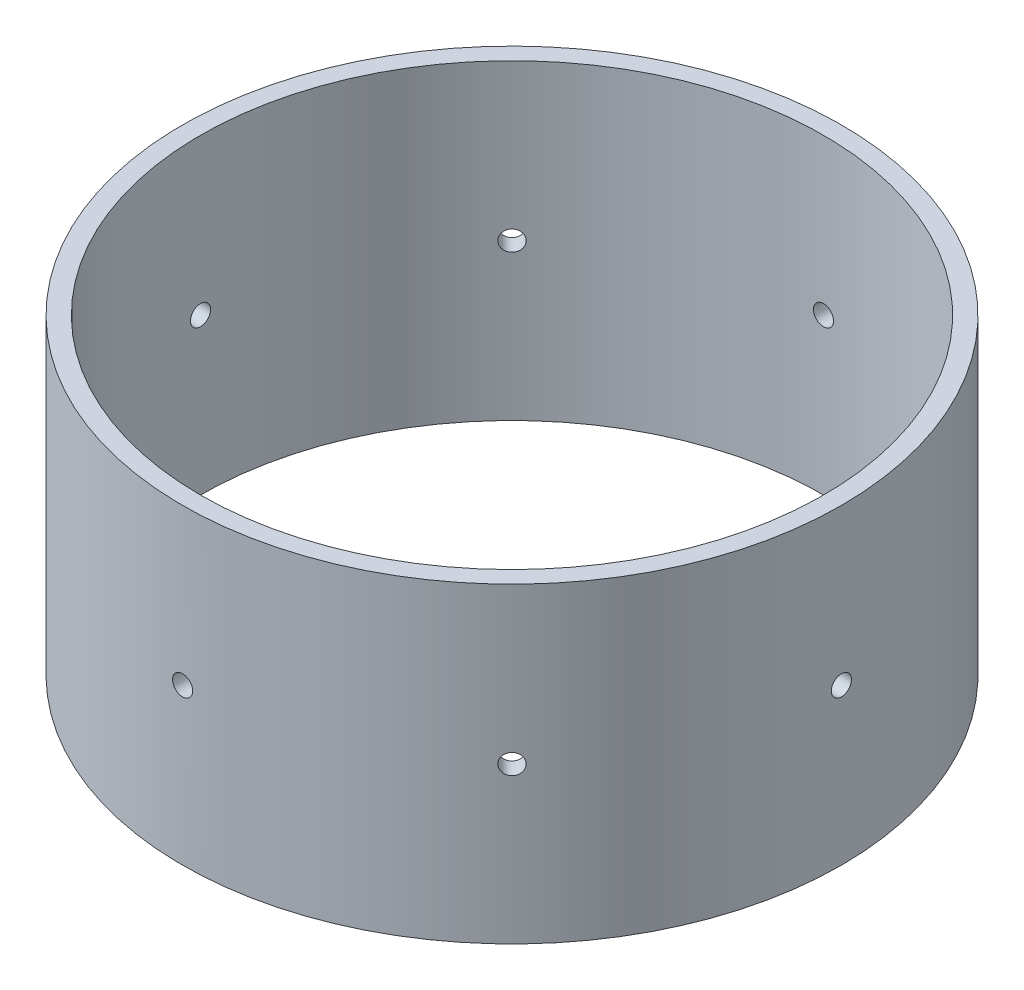
SolidWorks part; units mm, degrees
material "Hexcel AS4C (3000 Filaments)"
ref_plane "Front Plane" through (0, 0, 0) normal (0, 0, 1) x (1, 0, 0)
ref_plane "Top Plane" through (0, 0, 0) normal (0, 1, 0) x (1, 0, 0)
ref_plane "Right Plane" through (0, 0, 0) normal (1, 0, 0) x (0, 0, -1)
sketch "Sketch1" plane through (0, 0, 0) normal (0, 1, 0) x (1, 0, 0)
  circle A0 centre (0, 0) radius 50.8
  dimension "D1" = 101.6
extrude "Extrude-Thin1" add sketch "Sketch1" along normal blind 50.8 thin
ref_plane "Plane1" through (0, 0, 53.721) normal (0, 0, 1) x (1, 0, 0)
sketch "Sketch2" plane through (0, 0, 53.721) normal (0, 0, 1) x (1, 0, 0)
  line L0 (0, 50.8) -> (0, 0) construction
  line L1 (53.721, 50.8) -> (-53.721, 50.8) construction
  circle A0 centre (0, 25.4) radius 1.6383
  dimension "D1" = 3.2766
extrude "Cut-Extrude1" cut sketch "Sketch2" against normal up to next
pattern_circular "CirPattern1" count 8 over 360 about axis through (0, 50.8, 0) along (0, -1, 0) of "Cut-Extrude1"
